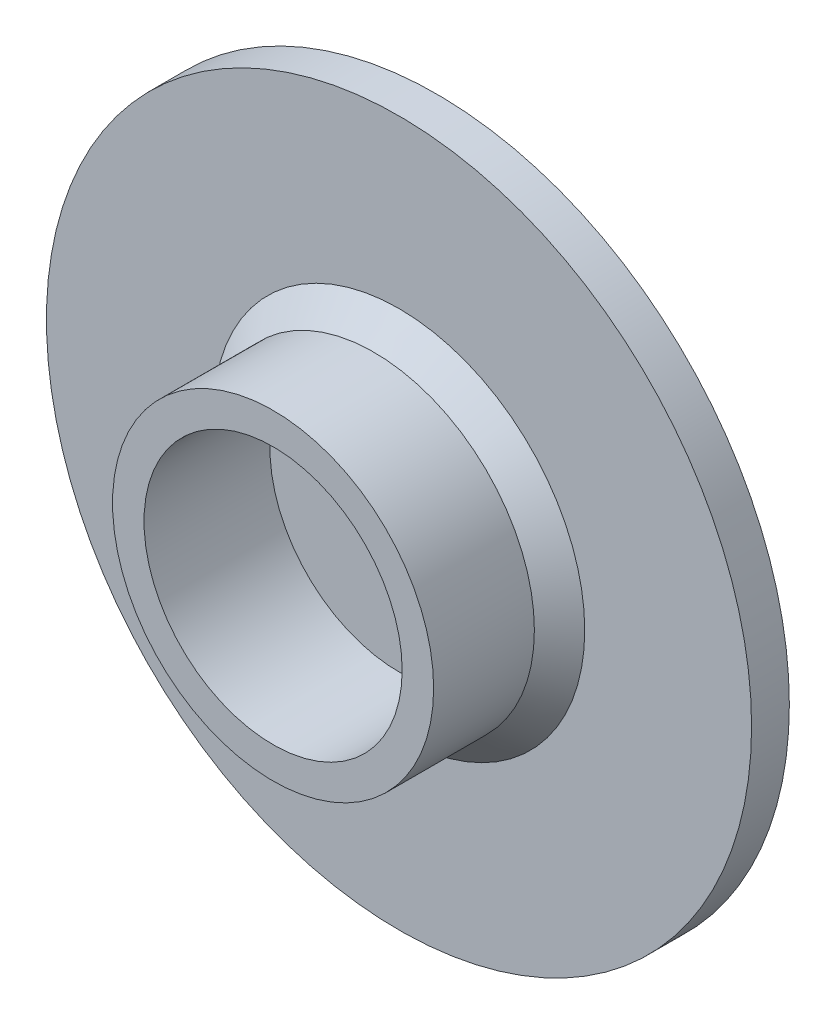
SolidWorks part; units mm, degrees
ref_plane "Front" through (0, 0, 0) normal (0, 0, 1) x (1, 0, 0)
ref_plane "Top" through (0, 0, 0) normal (0, 1, 0) x (1, 0, 0)
ref_plane "Right" through (0, 0, 0) normal (1, 0, 0) x (0, 0, -1)
sketch "Esquisse1" plane through (0, 0, 0) normal (0, 0, 1) x (1, 0, 0)
  circle A0 centre (0, 0) radius 28
  dimension "D1" = 56
extrude "Boss.-Extru.1" add sketch "Esquisse1" along normal blind 3
sketch "Esquisse2" plane through (0, 0, 3) normal (0, 0, 1) x (1, 0, 0)
  circle A0 centre (0, 0) radius 3
  dimension "D1" = 6
extrude "Enlèv. mat.-Extru.1" cut sketch "Esquisse2" against normal through all both and the other way through all
sketch "Esquisse3" plane through (0, 0, 3) normal (0, 0, 1) x (1, 0, 0)
  circle A0 centre (0, 0) radius 10.25
  circle A1 centre (0, 0) radius 12.75
  dimension "D1" = 20.5
  dimension "D2" = 2.5
extrude "Boss.-Extru.2" add sketch "Esquisse3" along normal blind 10
chamfer "Chanfrein1" distance 2 angle 45 1 edges at (12.75, 0, 3)
